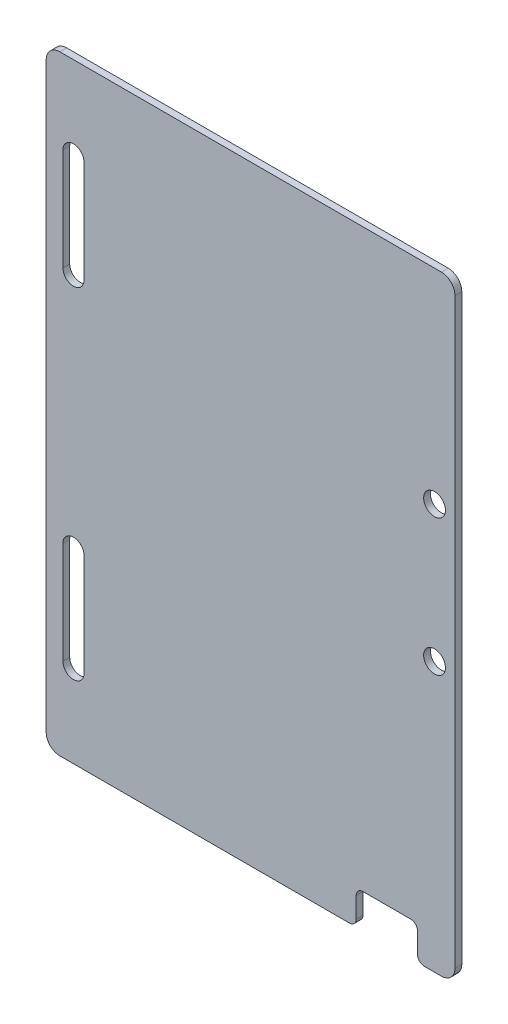
SolidWorks part; units mm, degrees
material "Thornel Mat VMA"
ref_plane "前视基准面" through (0, 0, 0) normal (0, 0, 1) x (1, 0, 0)
ref_plane "上视基准面" through (0, 0, 0) normal (0, 1, 0) x (1, 0, 0)
ref_plane "右视基准面" through (0, 0, 0) normal (1, 0, 0) x (0, 0, -1)
other "Configuration Table"
sketch "草图1" plane through (0, 0, 0) normal (0, 0, 1) x (1, 0, 0)
  line L0 (27, 44.75) -> (27, -44.75) construction
  line L1 (-30, -44.75) -> (30, -44.75)
  line L2 (-30, -44.75) -> (-30, 44.75)
  line L3 (-30, 44.75) -> (30, 44.75)
  line L4 (30, -44.75) -> (30, 44.75)
  line L5 (-30, -44.75) -> (30, 44.75) construction
  line L6 (-30, 44.75) -> (30, -44.75) construction
  circle A0 centre (27, 14.75) radius 1.6
  circle A1 centre (27, -5.25) radius 1.6
  point P0 (0, 0)
  point P12 (0, 0)
  dimension "D2" = 89.5
  dimension "D3" = 20
  dimension "D5" = 3.2
  dimension "D6" = 30
  dimension "D1" = 3
  dimension "D4" = 57
extrude "凸台-拉伸1" add sketch "草图1" along normal blind 1
sketch "草图2" plane through (0, 0, 1) normal (0, 0, 1) x (1, 0, 0)
  line L0 (-26, 32.5) -> (-26, 17.5) construction
  line L1 (-24.45, 32.5) -> (-24.45, 17.5)
  line L2 (-27.55, 32.5) -> (-27.55, 17.5)
  line L3 (-26, -17.5) -> (-26, -32.5) construction
  line L4 (-24.45, -17.5) -> (-24.45, -32.5)
  line L5 (-27.55, -17.5) -> (-27.55, -32.5)
  line L6 (0, 0) -> (50000, 0) construction
  line L7 (-30, 44.75) -> (-30, -44.75) construction
  arc A0 (-24.45, 32.5) -> (-27.55, 32.5) centre (-26, 32.5) ccw
  arc A1 (-27.55, 17.5) -> (-24.45, 17.5) centre (-26, 17.5) ccw
  arc A2 (-24.45, -17.5) -> (-27.55, -17.5) centre (-26, -17.5) ccw
  arc A3 (-27.55, -32.5) -> (-24.45, -32.5) centre (-26, -32.5) ccw
  point P2 (-26, 25)
  point P8 (-26, -25)
  dimension "D4" = 1.55
  dimension "D1" = 25
  dimension "D2" = 15
  dimension "D3" = 4
extrude "切除-拉伸1" cut sketch "草图2" against normal blind 10
fillet "圆角1" radius 2 4 edges at (30, -44.75, 0.5) (-30, -44.75, 0.5) (30, 44.75, 0.5) (-30, 44.75, 0.5)
sketch "草图3" plane through (0, 0, 0) normal (0, 0, -1) x (-1, 0, 0)
  line L0 (28, -44.75) -> (-28, -44.75) construction
  line L1 (-24.5, -49.75) -> (-15.5, -49.75)
  line L2 (-24.5, -49.75) -> (-24.5, -39.75)
  line L3 (-24.5, -39.75) -> (-15.5, -39.75)
  line L4 (-15.5, -49.75) -> (-15.5, -39.75)
  line L5 (-24.5, -49.75) -> (-15.5, -39.75) construction
  line L6 (-24.5, -39.75) -> (-15.5, -49.75) construction
  line L7 (-30, -42.75) -> (-30, 42.75) construction
  point P0 (-20, -44.75)
  dimension "D1" = 10
  dimension "D2" = 9
  dimension "D3" = 5
extrude "切除-拉伸2" cut sketch "草图3" against normal blind 10
fillet "圆角2" radius 1 4 edges at (24.5, -39.75, 0.5) (15.5, -39.75, 0.5) (15.5, -44.75, 0.5) (24.5, -44.75, 0.5)
